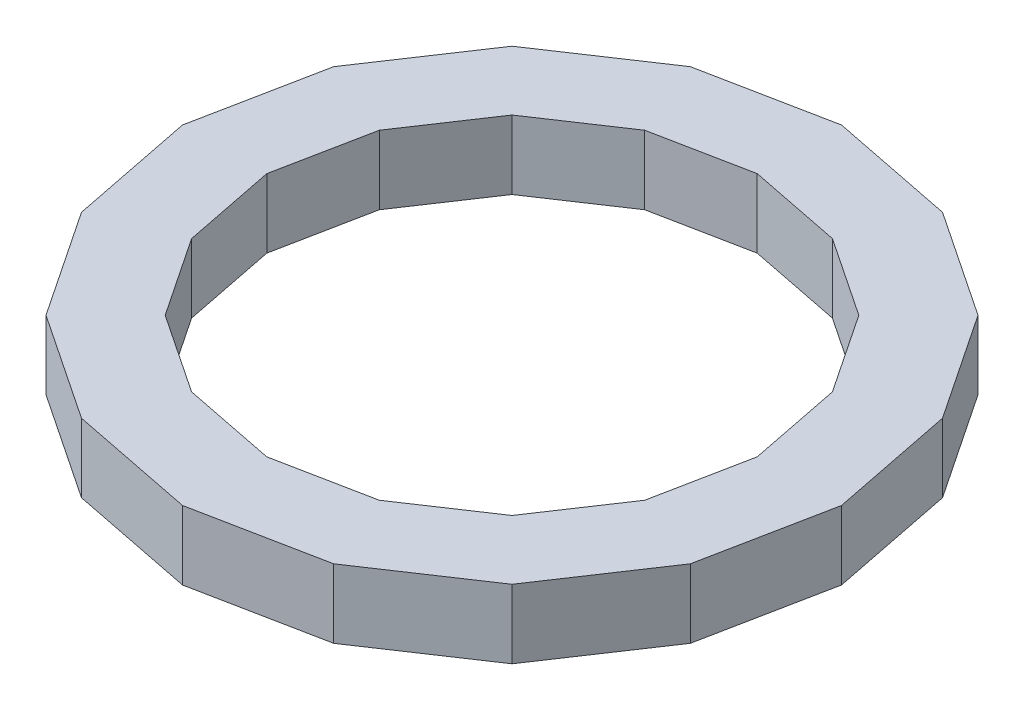
SolidWorks part; units mm, degrees
ref_plane "Front Plane" through (0, 0, 0) normal (0, 0, 1) x (1, 0, 0)
ref_plane "Top Plane" through (0, 0, 0) normal (0, 1, 0) x (1, 0, 0)
ref_plane "Right Plane" through (0, 0, 0) normal (1, 0, 0) x (0, 0, -1)
sketch "Sketch1" plane through (0, 0, 0) normal (0, 1, 0) x (1, 0, 0)
  line L1 (67.8294, 0) -> (62.6662, 25.9572)
  line L2 (62.6662, 25.9572) -> (47.9626, 47.9626)
  line L3 (47.9626, 47.9626) -> (25.9572, 62.6662)
  line L4 (25.9572, 62.6662) -> (0, 67.8294)
  line L5 (0, 67.8294) -> (-25.9572, 62.6662)
  line L6 (-25.9572, 62.6662) -> (-47.9626, 47.9626)
  line L7 (-47.9626, 47.9626) -> (-62.6662, 25.9572)
  line L8 (-62.6662, 25.9572) -> (-67.8294, 0)
  line L9 (-67.8294, 0) -> (-62.6662, -25.9572)
  line L10 (-62.6662, -25.9572) -> (-47.9626, -47.9626)
  line L11 (-47.9626, -47.9626) -> (-25.9572, -62.6662)
  line L12 (-25.9572, -62.6662) -> (0, -67.8294)
  line L13 (0, -67.8294) -> (25.9572, -62.6662)
  line L14 (25.9572, -62.6662) -> (47.9626, -47.9626)
  line L15 (47.9626, -47.9626) -> (62.6662, -25.9572)
  line L16 (62.6662, -25.9572) -> (67.8294, 0)
  line L17 (91.1373, 0) -> (84.1999, 34.8767)
  line L18 (84.1999, 34.8767) -> (64.4438, 64.4438)
  line L19 (64.4438, 64.4438) -> (34.8767, 84.1999)
  line L20 (34.8767, 84.1999) -> (0, 91.1373)
  line L21 (0, 91.1373) -> (-34.8767, 84.1999)
  line L22 (-34.8767, 84.1999) -> (-64.4438, 64.4438)
  line L23 (-64.4438, 64.4438) -> (-84.1999, 34.8767)
  line L24 (-84.1999, 34.8767) -> (-91.1373, 0)
  line L25 (-91.1373, 0) -> (-84.1999, -34.8767)
  line L26 (-84.1999, -34.8767) -> (-64.4438, -64.4438)
  line L27 (-64.4438, -64.4438) -> (-34.8767, -84.1999)
  line L28 (-34.8767, -84.1999) -> (0, -91.1373)
  line L29 (0, -91.1373) -> (34.8767, -84.1999)
  line L30 (34.8767, -84.1999) -> (64.4438, -64.4438)
  line L31 (64.4438, -64.4438) -> (84.1999, -34.8767)
  line L32 (84.1999, -34.8767) -> (91.1373, 0)
  circle A0 centre (0, 0) radius 66.5261 construction
  circle A1 centre (0, 0) radius 89.3861 construction
  dimension "D1" = 22.86
  dimension "D2" = 35.56
extrude "Boss-Extrude1" add sketch "Sketch1" along normal blind 19.05
